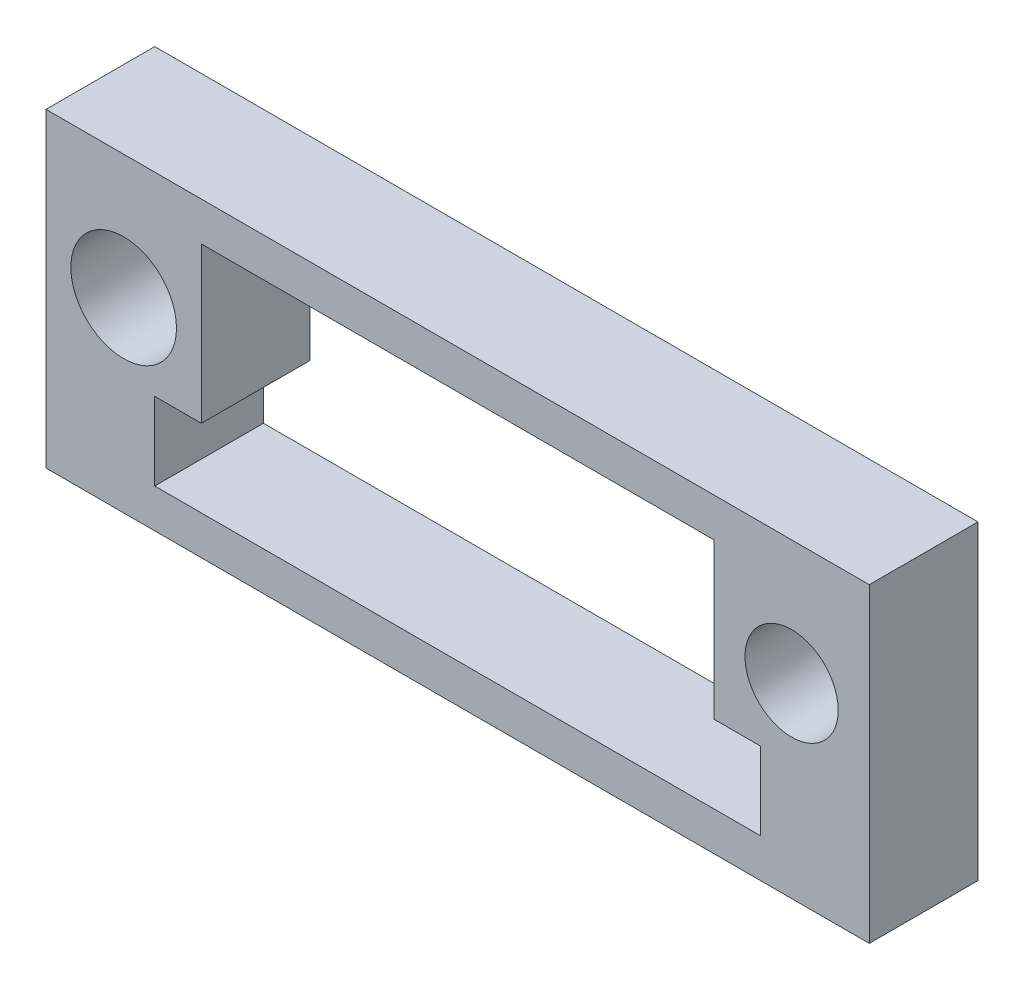
SolidWorks part; units mm, degrees
ref_plane "Front Plane" through (0, 0, 0) normal (0, 0, 1) x (1, 0, 0)
ref_plane "Top Plane" through (0, 0, 0) normal (0, 1, 0) x (1, 0, 0)
ref_plane "Right Plane" through (0, 0, 0) normal (1, 0, 0) x (0, 0, -1)
sketch "Sketch1" plane through (0, 0, 0) normal (0, 0, 1) x (1, 0, 0)
  line L0 (-63.1225, -9.6287) -> (-30.1225, -9.6287)
  line L1 (-30.1225, -9.6287) -> (-30.1225, -24.6287)
  line L2 (-30.1225, -24.6287) -> (-63.1225, -24.6287)
  line L3 (-63.1225, -24.6287) -> (-63.1225, -9.6287)
  line L4 (-73.1225, -7.1287) -> (-20.1225, -7.1287)
  line L5 (-20.1225, -7.1287) -> (-20.1225, -27.1287)
  line L6 (-20.1225, -27.1287) -> (-73.1225, -27.1287)
  line L7 (-73.1225, -27.1287) -> (-73.1225, -7.1287)
  line L8 (-63.1225, -19.6287) -> (-66.1225, -19.6287)
  line L9 (-66.1225, -19.6287) -> (-66.1225, -24.6287)
  line L10 (-30.1225, -19.6287) -> (-27.1225, -19.6287)
  line L11 (-27.1225, -19.6287) -> (-27.1225, -24.6287)
  line L12 (-66.1225, -24.6287) -> (-63.1225, -24.6287)
  line L13 (-30.1225, -24.6287) -> (-27.1225, -24.6287)
  circle A0 centre (-68.1225, -15.1287) radius 3.4
  circle A1 centre (-25.1225, -15.1287) radius 3
  dimension "D12" = 5
  dimension "D16" = 5
  dimension "D1" = 15
  dimension "D2" = 33
  dimension "D3" = 15
  dimension "D4" = 33
  dimension "D5" = 15
  dimension "D6" = 0
  dimension "D7" = 20
  dimension "D8" = 20
  dimension "D9" = 2.5
  dimension "D10" = 10
  dimension "D11" = 10
  dimension "D13" = 12
  dimension "D14" = 5
  dimension "D15" = 12
  dimension "D17" = 3
  dimension "D18" = 3
  dimension "D19" = 5
  dimension "D20" = 3
  dimension "D21" = 3
extrude "Boss-Extrude2" add sketch "Sketch1" along normal blind 7 contours L7 L6 L5 L4 A1 A0 L13 L2 L12 L9 L8 L3 L0 L1 L10 L11
